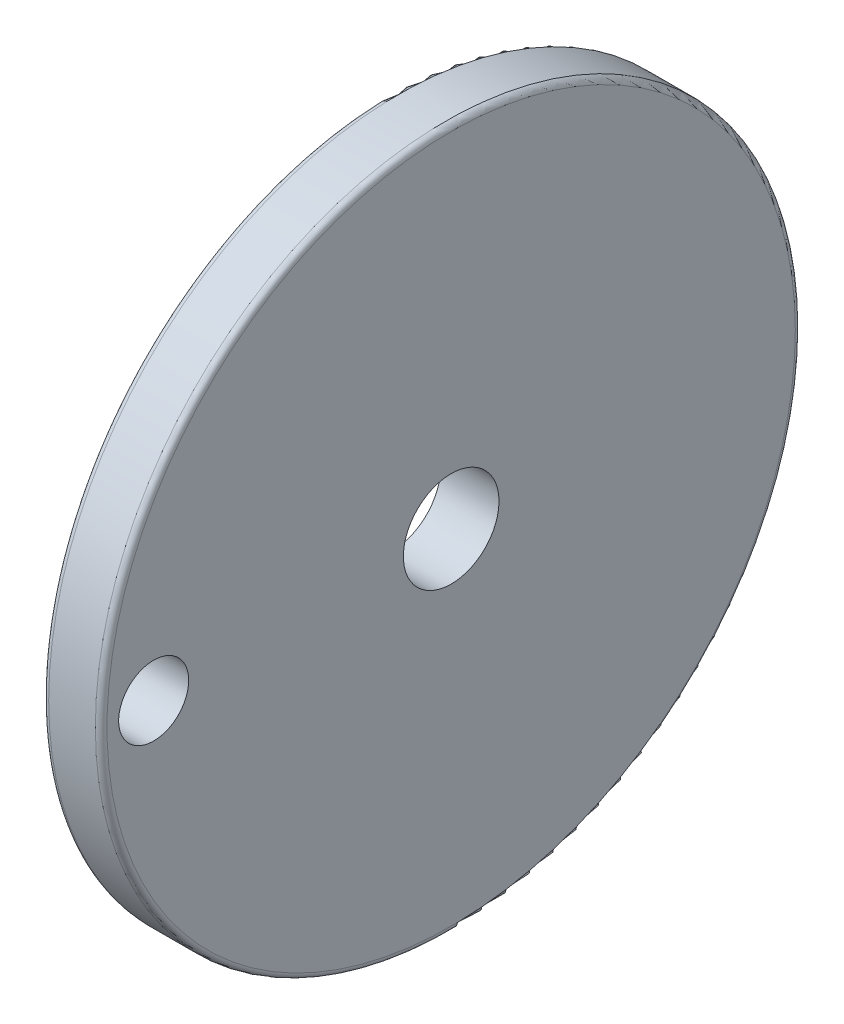
SolidWorks part; units mm, degrees
ref_plane "Front Plane" through (0, 0, 0) normal (0, 0, 1) x (1, 0, 0)
ref_plane "Top Plane" through (0, 0, 0) normal (0, 1, 0) x (1, 0, 0)
ref_plane "Right Plane" through (0, 0, 0) normal (1, 0, 0) x (0, 0, -1)
sketch "Sketch1" plane through (0, 0, 0) normal (1, 0, 0) x (0, 0, -1)
  line L0 (0, 0) -> (-30, 0) construction
  circle A0 centre (0, 0) radius 30
  circle A1 centre (-25.5, 0) radius 3
  circle A2 centre (0, 0) radius 4.1
  dimension "D1" = 8.2
  dimension "60" = 60
  dimension "D2" = 6
  dimension "D3" = 25.5
extrude "Boss-Extrude1" add sketch "Sketch1" along normal blind 5
fillet "Fillet1" radius 0.5 2 edges at (5, 0, -30) (0, 0, -30)
